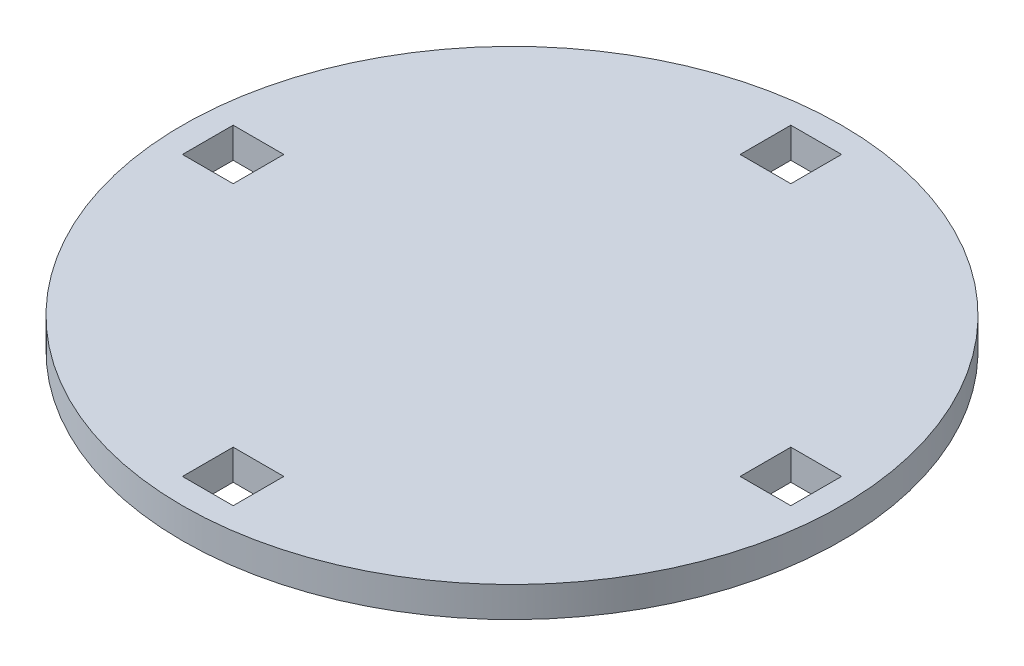
SolidWorks part; units mm, degrees
material "Mahogany"
ref_plane "Front Plane" through (0, 0, 0) normal (0, 0, 1) x (1, 0, 0)
ref_plane "Top Plane" through (0, 0, 0) normal (0, 1, 0) x (1, 0, 0)
ref_plane "Right Plane" through (0, 0, 0) normal (1, 0, 0) x (0, 0, -1)
sketch "Sketch1" plane through (0, 0, 0) normal (0, 1, 0) x (1, 0, 0)
  circle A0 centre (0, 0) radius 32.5
  dimension "D1" = 65
extrude "Boss-Extrude1" add sketch "Sketch1" along normal blind 3
sketch "Sketch2" plane through (0, 0, 0) normal (0, 1, 0) x (1, 0, 0)
  line L5 (2.5, -30) -> (-2.5, -30)
  line L6 (25, 2.5) -> (30, 2.5)
  line L18 (25, 2.5) -> (25, -2.5)
  line L19 (25, -2.5) -> (30, -2.5)
  line L20 (30, 2.5) -> (30, -2.5)
  line L21 (25, 2.5) -> (30, -2.5) construction
  line L22 (25, -2.5) -> (30, 2.5) construction
  line L23 (2.5, -25) -> (2.5, -30)
  line L24 (2.5, -25) -> (-2.5, -25)
  line L25 (-2.5, -25) -> (-2.5, -30)
  line L26 (-30, -2.5) -> (-30, 2.5)
  line L27 (-25, -2.5) -> (-30, -2.5)
  line L28 (-25, -2.5) -> (-25, 2.5)
  line L29 (-25, 2.5) -> (-30, 2.5)
  line L30 (-2.5, 30) -> (2.5, 30)
  line L31 (-2.5, 25) -> (-2.5, 30)
  line L32 (-2.5, 25) -> (2.5, 25)
  line L33 (2.5, 25) -> (2.5, 30)
  circle A0 centre (0, 0) radius 27.5 construction
  circle A1 centre (0, 0) radius 27.5 construction
  circle A2 centre (0, 0) radius 27.5 construction
  circle A3 centre (0, 0) radius 27.5 construction
  point P3 (27.5, 0)
  point P23 (0, 0)
  point P27 (0, 0)
  dimension "D1" = 55
  dimension "D2" = 5
  dimension "D3" = 4
  dimension "D4" = 5
extrude "Cut-Extrude1" cut sketch "Sketch2" along normal blind 10 and the other way through all
